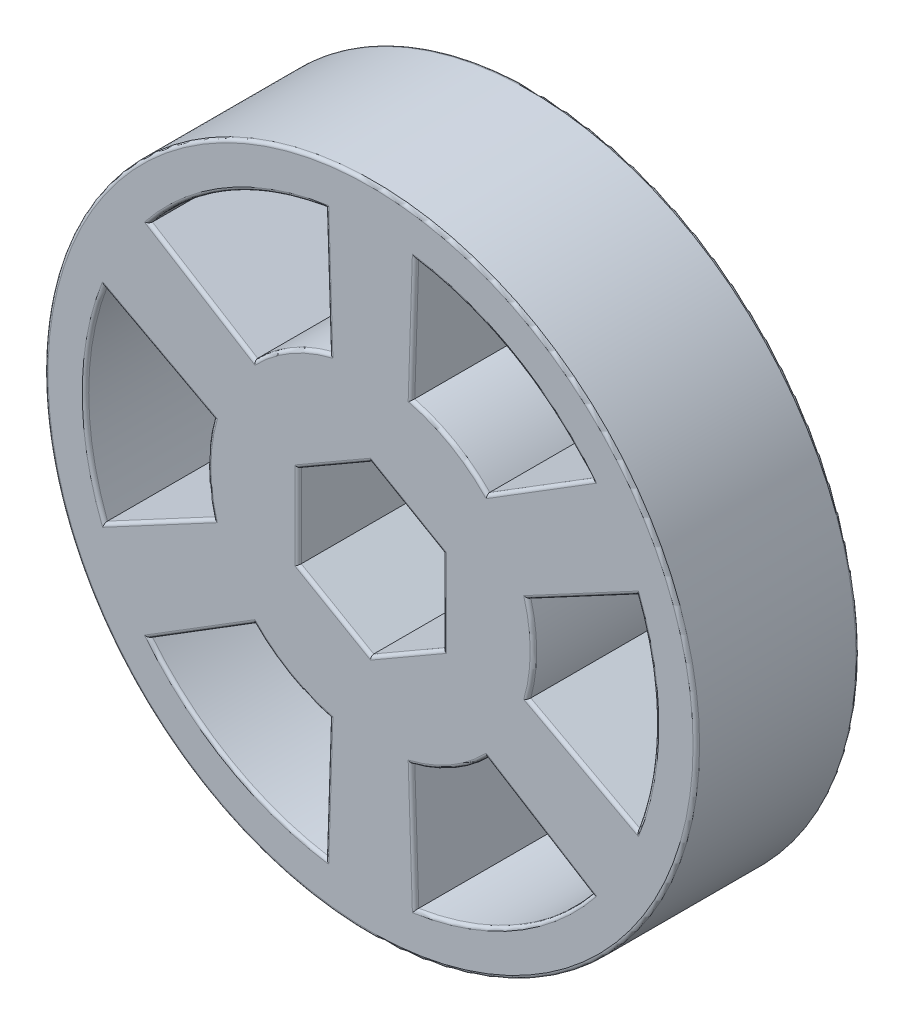
SolidWorks part; units mm, degrees
material "POLYURETHANE (11671)"
ref_plane "Front Plane" through (0, 0, 0) normal (0, 0, 1) x (1, 0, 0)
ref_plane "Top Plane" through (0, 0, 0) normal (0, 1, 0) x (1, 0, 0)
ref_plane "Right Plane" through (0, 0, 0) normal (1, 0, 0) x (0, 0, -1)
sketch "Sketch1" plane through (0, 0, 0) normal (0, 0, 1) x (1, 0, 0)
  circle A0 centre (0, 0) radius 25.4
  dimension "D1" = 50.8
extrude "Boss-Extrude1" add sketch "Sketch1" along normal mid plane 12.7
sketch "Sketch2" plane through (0, 0, 6.35) normal (0, 0, 1) x (1, 0, 0)
  line L0 (-5.6515, 3.2629) -> (-5.6515, -3.2629)
  line L1 (-5.6515, -3.2629) -> (0, -6.5258)
  line L2 (0, -6.5258) -> (5.6515, -3.2629)
  line L3 (5.6515, -3.2629) -> (5.6515, 3.2629)
  line L4 (5.6515, 3.2629) -> (0, 6.5258)
  line L5 (0, 6.5258) -> (-5.6515, 3.2629)
  point P2 (0, 0)
  point P7 (-5.6515, 0)
  point P9 (5.6515, 0)
  dimension "D1" = 11.303
  dimension "D2" = 11.303
extrude "Cut-Extrude1" cut sketch "Sketch2" against normal through all
sketch "Sketch3" plane through (0, 0, 6.35) normal (0, 0, 1) x (1, 0, 0)
  line L0 (9.0487, -8.9113) -> (17.2537, -14.0093)
  line L1 (12.2418, 3.3808) -> (20.7593, 7.9375)
  line L2 (12.2418, -3.3808) -> (20.7593, -7.9375)
  line L3 (3.1931, -12.292) -> (3.5056, -21.9468)
  line L4 (-3.1931, -12.292) -> (-3.5056, -21.9468)
  line L5 (-9.0487, -8.9113) -> (-17.2537, -14.0093)
  line L6 (-12.2418, -3.3808) -> (-20.7593, -7.9375)
  line L7 (-12.2418, 3.3808) -> (-20.7593, 7.9375)
  line L8 (-9.0487, 8.9113) -> (-17.2537, 14.0093)
  line L9 (-3.1931, 12.292) -> (-3.5056, 21.9468)
  line L10 (3.1931, 12.292) -> (3.5056, 21.9468)
  line L11 (9.0487, 8.9113) -> (17.2537, 14.0093)
  arc A0 (20.7593, -7.9375) -> (20.7593, 7.9375) centre (0, 0) ccw
  circle A1 centre (0, 0) radius 25.4 construction
  arc A2 (12.2418, -3.3808) -> (12.2418, 3.3808) centre (0, 0) ccw
  arc A3 (3.5056, -21.9468) -> (17.2537, -14.0093) centre (0, 0) ccw
  arc A4 (3.1931, -12.292) -> (9.0487, -8.9113) centre (0, 0) ccw
  arc A5 (-17.2537, -14.0093) -> (-3.5056, -21.9468) centre (0, 0) ccw
  arc A6 (-9.0487, -8.9113) -> (-3.1931, -12.292) centre (0, 0) ccw
  arc A7 (-20.7593, 7.9375) -> (-20.7593, -7.9375) centre (0, 0) ccw
  arc A8 (-12.2418, 3.3808) -> (-12.2418, -3.3808) centre (0, 0) ccw
  arc A9 (-3.5056, 21.9468) -> (-17.2537, 14.0093) centre (0, 0) ccw
  arc A10 (-3.1931, 12.292) -> (-9.0487, 8.9113) centre (0, 0) ccw
  arc A11 (17.2537, 14.0093) -> (3.5056, 21.9468) centre (0, 0) ccw
  arc A12 (9.0487, 8.9113) -> (3.1931, 12.292) centre (0, 0) ccw
  point P31 (0, 0)
  dimension "D1" = 3.175
  dimension "D4" = 25.4
  dimension "D2" = 15.875
  dimension "D3" = 7.9375
  dimension "D5" = 6
extrude "Cut-Extrude2" cut sketch "Sketch3" against normal through all
fillet "Fillet2" radius 0.254 31 edges at (25.4, 0, -6.35) (5.6515, 0, -6.35) (2.8257, -4.8943, -6.35) (-2.8258, -4.8943, -6.35) (-5.6515, 0, -6.35) (-2.8258, 4.8943, -6.35) (2.8257, 4.8943, -6.35) (22.225, 0, -6.35) (16.5005, -5.6591, -6.35) (12.7, 0, -6.35) (16.5005, 5.6591, -6.35) (11.1125, 19.2474, -6.35) (13.1512, 11.4603, -6.35) (6.35, 10.9985, -6.35) (3.3493, 17.1194, -6.35) (-11.1125, 19.2474, -6.35) (-3.3493, 17.1194, -6.35) (-6.35, 10.9985, -6.35) (-13.1512, 11.4603, -6.35) (-22.225, 0, -6.35) (-16.5005, 5.6591, -6.35) (-12.7, 0, -6.35) (-16.5005, -5.6591, -6.35) (-11.1125, -19.2474, -6.35) (-13.1512, -11.4603, -6.35) (-6.35, -10.9985, -6.35) (-3.3493, -17.1194, -6.35) (11.1125, -19.2474, -6.35) (3.3493, -17.1194, -6.35) (6.35, -10.9985, -6.35) (13.1512, -11.4603, -6.35)
fillet "Fillet3" radius 0.254 31 edges at (25.4, 0, 6.35) (-5.6515, 0, 6.35) (-2.8258, -4.8943, 6.35) (2.8257, -4.8943, 6.35) (5.6515, 0, 6.35) (2.8257, 4.8943, 6.35) (-2.8258, 4.8943, 6.35) (16.5005, -5.6591, 6.35) (22.225, 0, 6.35) (16.5005, 5.6591, 6.35) (12.7, 0, 6.35) (13.1512, 11.4603, 6.35) (11.1125, 19.2474, 6.35) (3.3493, 17.1194, 6.35) (6.35, 10.9985, 6.35) (-3.3493, 17.1194, 6.35) (-11.1125, 19.2474, 6.35) (-13.1512, 11.4603, 6.35) (-6.35, 10.9985, 6.35) (-16.5005, 5.6591, 6.35) (-22.225, 0, 6.35) (-16.5005, -5.6591, 6.35) (-12.7, 0, 6.35) (-13.1512, -11.4603, 6.35) (-11.1125, -19.2474, 6.35) (-3.3493, -17.1194, 6.35) (-6.35, -10.9985, 6.35) (3.3493, -17.1194, 6.35) (11.1125, -19.2474, 6.35) (13.1512, -11.4603, 6.35) (6.35, -10.9985, 6.35)
